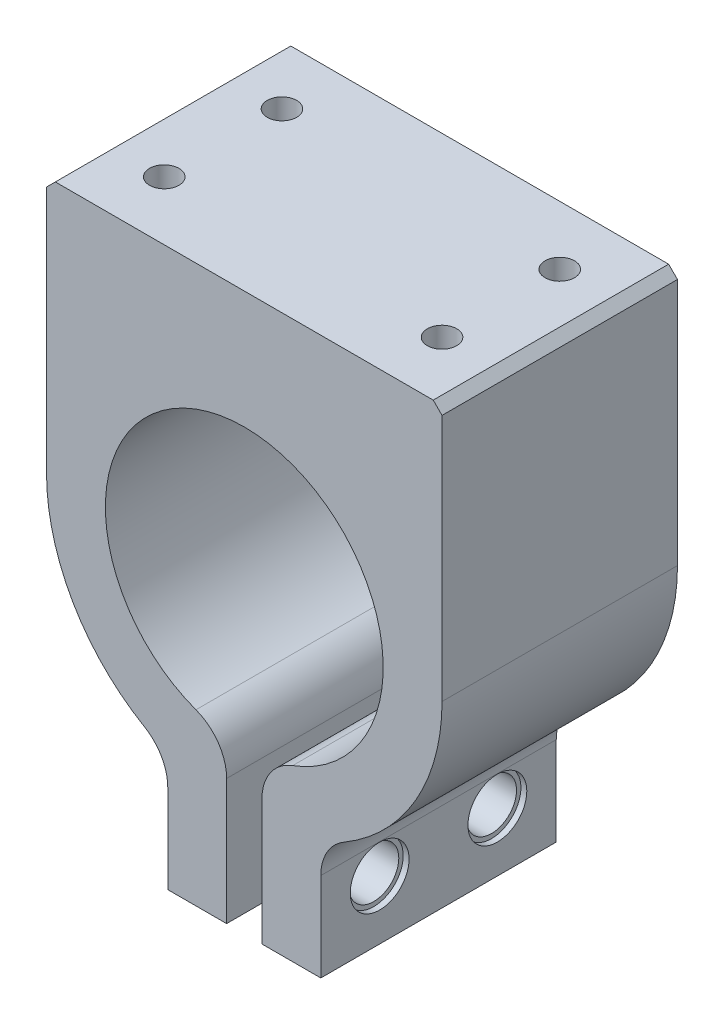
SolidWorks part; units mm, degrees
ref_plane "Front Plane" through (0, 0, 0) normal (0, 0, 1) x (1, 0, 0)
ref_plane "Top Plane" through (0, 0, 0) normal (0, 1, 0) x (1, 0, 0)
ref_plane "Right Plane" through (0, 0, 0) normal (1, 0, 0) x (0, 0, -1)
sketch "Sketch1" plane through (0, 0, 0) normal (0, 0, 1) x (1, 0, 0)
  line L0 (-16.8, 0) -> (-16.8, 21.8)
  line L1 (-16.8, 21.8) -> (16.8, 21.8)
  line L2 (16.8, 21.8) -> (16.8, 0)
  line L3 (0, 0) -> (0, -50000) construction
  line L4 (-1.5, -16.7329) -> (-1.5, -25.4916)
  line L5 (1.5, -16.7329) -> (1.5, -25.4916)
  line L6 (-1.5, -25.4916) -> (-6.5, -25.4916)
  line L7 (1.5, -25.4916) -> (6.5, -25.4916)
  line L8 (-6.5, -25.4916) -> (-6.5, -15.4916)
  line L9 (6.5, -25.4916) -> (6.5, -15.4916)
  line L10 (-1.5, -16.7329) -> (-1.5, -11.7043)
  line L11 (1.5, -16.7329) -> (1.5, -11.7043)
  arc A0 (16.8, 0) -> (-16.8, 0) centre (0, 0) cw
  circle A1 centre (0, 0) radius 11.8
  point P7 (0, 11.8)
  dimension "D1" = 23.6
  dimension "D2" = 5
  dimension "D3" = 10
  dimension "D4" = 3
  dimension "D5" = 5
  dimension "D6" = 10
  dimension "D7" = 47.2916
extrude "Boss-Extrude1" add sketch "Sketch1" along normal mid plane 20 contours L9 A0 L5 L7 | L1 L3 A1 L11 A0 L2 | L3 L1 L0 A0 L10 A1 | L4 A0 L8 L6
sketch "Sketch2" plane through (0, 21.8, 0) normal (0, 1, 0) x (1, 0, 0)
  line L0 (-16.8, 0) -> (-11.8, 0)
  line L1 (11.8, -5) -> (-11.8, -5)
  line L2 (11.8, -5) -> (11.8, 5)
  line L3 (11.8, 5) -> (-11.8, 5)
  line L4 (-11.8, -5) -> (-11.8, 5)
  line L5 (11.8, -5) -> (-11.8, 5) construction
  line L6 (11.8, 5) -> (-11.8, -5) construction
  line L7 (-16.8, -10) -> (-16.8, 10) construction
  line L8 (0, 5) -> (0, 10)
  line L9 (-16.8, 10) -> (16.8, 10) construction
  point P0 (0, 0)
  point P7 (-11.8, 5)
  point P8 (11.8, 5)
  point P9 (11.8, -5)
  point P10 (-11.8, -5)
  dimension "D1" = 10
hole_wizard "Ø2.5 (2.5) Diameter Hole1" positions "Sketch2" profile "Sketch3" hole size "Ø2.5" standard "ANSI Metric"
sketch "Sketch3" plane through (-11.8, 21.8, 5) normal (1, 0, 0) x (0, 0, 1)
  line L0 (0, 0) -> (0, 11.25)
  line L1 (0, 11.25) -> (1.25, 10)
  line L2 (1.25, 10) -> (1.25, 0)
  line L5 (1.25, 0) -> (0, 0)
  line L10 (0, 11.25) -> (-1.25, 10) construction
  line L11 (0, -6.35) -> (0, 107.95) construction
  dimension "Hole Dia." = 2.5
  dimension "Hole Depth" = 10
  dimension "Drill Angle" = 90
sketch "Sketch4" plane through (6.5, 0, 0) normal (1, 0, 0) x (0, 0, -1)
  line L0 (-5, -20.4916) -> (5, -20.4916)
  line L1 (10, -25.4916) -> (10, -15.4916) construction
  point P0 (10, -20.4916)
  point P3 (0, -20.4916)
  point P4 (-5, -20.4916)
  point P5 (5, -20.4916)
  dimension "D1" = 10
hole_wizard "CBORE for M5 Hex Head Machine Screw2" positions "Sketch4" profile "Sketch5" counterbore size "M5" standard "ANSI Metric"
sketch "Sketch5" plane through (6.5, -20.4916, -5) normal (0, 1, 0) x (0, 0, -1)
  line L0 (0, 0) -> (0, 6.2768)
  line L1 (0, 6.2768) -> (2.125, 5)
  line L2 (2.125, 5) -> (2.125, 0.5)
  line L3 (2.125, 0.5) -> (2.5, 0.5)
  line L4 (2.5, 0.5) -> (2.5, 0)
  line L5 (2.5, 0) -> (0, 0)
  line L10 (0, 6.2768) -> (-2.125, 5) construction
  line L11 (0, -6.35) -> (0, 107.95) construction
  dimension "Hole Dia." = 4.25
  dimension "Hole Depth" = 5
  dimension "C'Bore Dia." = 5
  dimension "C'Bore Depth" = 0.5
  dimension "Drill Angle" = 118
sketch "Sketch6" plane through (-6.5, 0, 0) normal (-1, 0, 0) x (0, 0, 1)
  point P0 (-5, -20.4916)
  point P1 (5, -20.4916)
hole_wizard "M3 Clearance Hole1" positions "Sketch6" profile "Sketch7" hole size "M3" standard "ANSI Metric"
sketch "Sketch7" plane through (-6.5, -20.4916, -5) normal (0, 1, 0) x (0, 0, 1)
  line L0 (0, 0) -> (0, 6.0215)
  line L1 (0, 6.0215) -> (1.7, 5)
  line L2 (1.7, 5) -> (1.7, 0)
  line L5 (1.7, 0) -> (0, 0)
  line L10 (0, 6.0215) -> (-1.7, 5) construction
  line L11 (0, -6.35) -> (0, 107.95) construction
  dimension "Hole Dia." = 3.4
  dimension "Hole Depth" = 5
  dimension "Drill Angle" = 118
fillet "Fillet1" radius 4 4 edges at (-6.5, -15.4916, 0) (6.5, -15.4916, 0) (-1.5, -11.7043, 0) (1.5, -11.7043, 0)
chamfer "Chamfer1" distance 0.75 angle 45 2 edges at (16.8, 21.8, 0) (-16.8, 21.8, 0)
